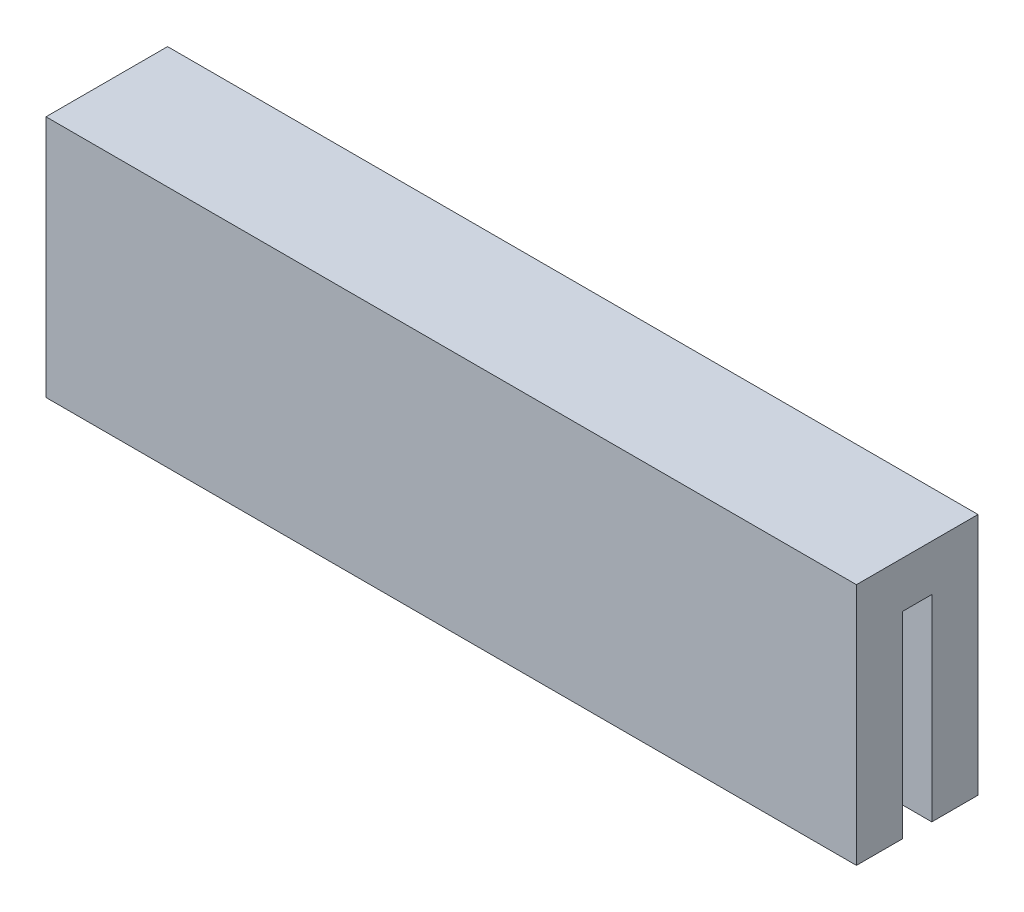
SolidWorks part; units mm, degrees
ref_plane "Plan de face" through (0, 0, 0) normal (0, 0, 1) x (1, 0, 0)
ref_plane "Plan de dessus" through (0, 0, 0) normal (0, 1, 0) x (1, 0, 0)
ref_plane "Plan de droite" through (0, 0, 0) normal (1, 0, 0) x (0, 0, -1)
sketch "Esquisse1" plane through (0, 0, 0) normal (0, 1, 0) x (1, 0, 0)
  line L1 (0, 0) -> (100, 0)
  line L2 (0, 0) -> (0, -15)
  line L3 (0, -15) -> (100, -15)
  line L4 (100, 0) -> (100, -15)
  dimension "D1" = 15
  dimension "D2" = 100
extrude "Boss.-Extru.1" add sketch "Esquisse1" along normal blind 30
sketch "Esquisse2" plane through (0, 0, 0) normal (0, -1, 0) x (1, 0, 0)
  line L0 (0, 0) -> (0, 15) construction
  line L1 (100, 15) -> (100, 0) construction
  line L2 (0, 9.3) -> (100, 9.3)
  line L3 (0, 9.3) -> (0, 5.7)
  line L4 (0, 5.7) -> (100, 5.7)
  line L5 (100, 9.3) -> (100, 5.7)
  point P0 (0, 9.3)
  point P1 (0, 5.7)
  dimension "D1" = 5.7
  dimension "D2" = 5.7
extrude "Enlèv. mat.-Extru.1" cut sketch "Esquisse2" against normal blind 24.3
